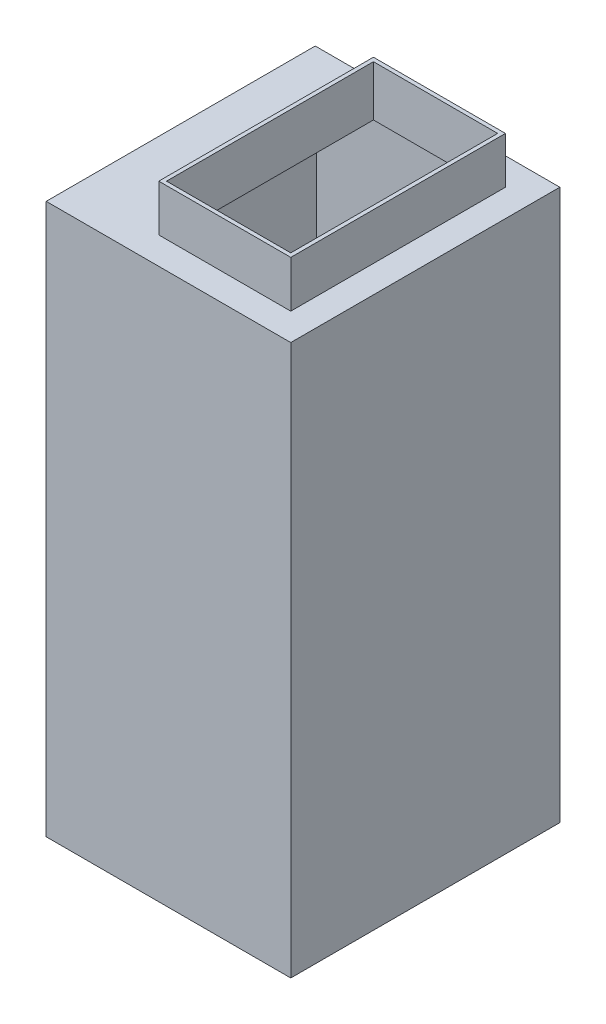
SolidWorks part; units mm, degrees
ref_plane "Plan de face" through (0, 0, 0) normal (0, 0, 1) x (1, 0, 0)
ref_plane "Plan de dessus" through (0, 0, 0) normal (0, 1, 0) x (1, 0, 0)
ref_plane "Plan de droite" through (0, 0, 0) normal (1, 0, 0) x (0, 0, -1)
sketch "Esquisse2" plane through (0, 0, 0) normal (0, 0, 1) x (1, 0, 0)
  line L1 (-100, 225) -> (100, 225)
  line L2 (-100, 225) -> (-100, -225)
  line L3 (-100, -225) -> (100, -225)
  line L4 (100, 225) -> (100, -225)
  point P4 (-100, 0)
  point P6 (0, -225)
  dimension "D1" = 200
  dimension "D2" = 450
extrude "Boss.-Extru.1" add sketch "Esquisse2" along normal mid plane 220
sketch "Esquisse3" plane through (0, 0, 0) normal (0, 0, 1) x (1, 0, 0)
  line L0 (100, -225) -> (100, 225) construction
  line L1 (-96.825, 221.825) -> (96.825, 221.825)
  line L2 (-96.825, 221.825) -> (-96.825, -221.825)
  line L3 (-96.825, -221.825) -> (96.825, -221.825)
  line L4 (96.825, 221.825) -> (96.825, -221.825)
  line L5 (-100, -225) -> (100, -225) construction
  line L6 (-100, 225) -> (-100, -225) construction
  line L7 (100, 225) -> (-100, 225) construction
  dimension "D1" = 3.175
  dimension "D2" = 3.175
  dimension "D3" = 3.175
  dimension "D4" = 3.175
extrude "Enlèv. mat.-Extru.1" cut sketch "Esquisse3" against normal mid plane 216
sketch "Esquisse5" plane through (0, 225, 0) normal (0, 1, 0) x (1, 0, 0)
  line L0 (100, 110) -> (-100, 110) construction
  line L1 (-30.175, 87.775) -> (77.775, 87.775)
  line L2 (-30.175, 87.775) -> (-30.175, -87.775)
  line L3 (-30.175, -87.775) -> (77.775, -87.775)
  line L4 (77.775, 87.775) -> (77.775, -87.775)
  line L5 (100, -110) -> (-100, -110) construction
  line L6 (100, -110) -> (100, 110) construction
  dimension "D1" = 22.225
  dimension "D2" = 22.225
  dimension "D3" = 22.225
  dimension "D4" = 107.95
extrude "Boss.-Extru.2" add sketch "Esquisse5" along normal blind 38.1
sketch "Esquisse4" plane through (0, 263.1, 0) normal (0, 1, 0) x (1, 0, 0)
  line L0 (100, -110) -> (100, 110) construction
  line L1 (-27, 84.6) -> (74.6, 84.6)
  line L2 (-27, 84.6) -> (-27, -84.6)
  line L3 (-27, -84.6) -> (74.6, -84.6)
  line L4 (74.6, 84.6) -> (74.6, -84.6)
  line L5 (100, 110) -> (-100, 110) construction
  line L6 (100, -110) -> (-100, -110) construction
  dimension "D1" = 25.4
  dimension "D2" = 25.4
  dimension "D3" = 25.4
  dimension "D4" = 101.6
extrude "Enlèv. mat.-Extru.2" cut sketch "Esquisse4" against normal blind 41.275
